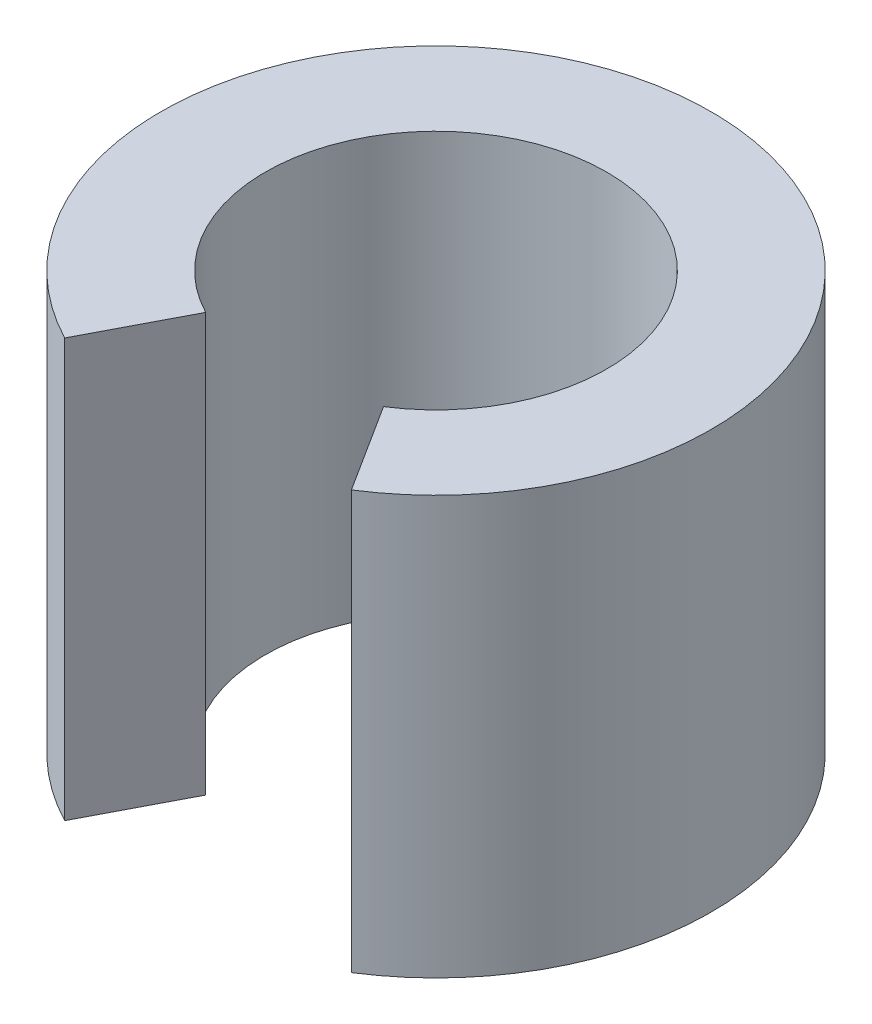
SolidWorks part; units mm, degrees
ref_plane "Front Plane" through (0, 0, 0) normal (0, 0, 1) x (1, 0, 0)
ref_plane "Top Plane" through (0, 0, 0) normal (0, 1, 0) x (1, 0, 0)
ref_plane "Right Plane" through (0, 0, 0) normal (1, 0, 0) x (0, 0, -1)
sketch "Sketch1" plane through (0, 0, 0) normal (0, 1, 0) x (1, 0, 0)
  line L0 (-1.1333, -2.1721) -> (-1.8271, -3.502)
  line L1 (1.3145, -2.0675) -> (2.1193, -3.3334)
  arc A0 (-1.1333, -2.1721) -> (1.3145, -2.0675) centre (0, 0) cw
  arc A1 (-1.8271, -3.502) -> (2.1193, -3.3334) centre (0, 0) cw
  dimension "D1" = 1.5
  dimension "D2" = 2.45
extrude "Boss-Extrude1" add sketch "Sketch1" along normal blind 6
